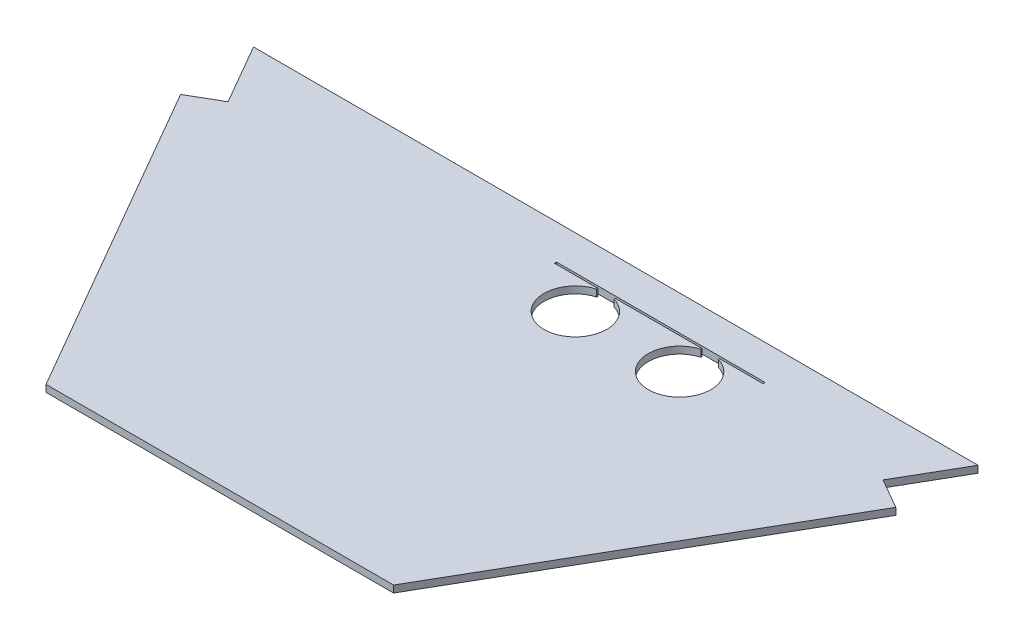
SolidWorks part; units mm, degrees
material "Ti-6Al-4VSolution treated and aged (SS)"
ref_plane "Front Plane" through (0, 0, 0) normal (0, 0, 1) x (1, 0, 0)
ref_plane "Top Plane" through (0, 0, 0) normal (0, 1, 0) x (1, 0, 0)
ref_plane "Right Plane" through (0, 0, 0) normal (1, 0, 0) x (0, 0, -1)
sketch "Sketch1" plane through (0, 0, 0) normal (0, 1, 0) x (1, 0, 0)
  line L1 (-271.1337, 569.6174) -> (771.1337, 569.6174)
  line L3 (500, 0) -> (0, 0)
  line L4 (0, 0) -> (-264.435, 458.0149)
  line L5 (-264.435, 458.0149) -> (-221.1337, 483.0149)
  line L6 (-221.1337, 483.0149) -> (-271.1337, 569.6174)
  line L7 (500, 0) -> (764.435, 458.0149)
  line L8 (764.435, 458.0149) -> (721.1337, 483.0149)
  line L9 (721.1337, 483.0149) -> (771.1337, 569.6174)
  dimension "D2" = 500
  dimension "D3" = 120
  dimension "D4" = 120
  dimension "D6" = 528.87
  dimension "D9" = 50
  dimension "D10" = 100
extrude "Boss-Extrude1" add sketch "Sketch1" along normal blind 10
sketch "Sketch2" plane through (0, 0, 0) normal (0, -1, 0) x (-1, 0, 0)
  line L0 (0, 0) -> (-500, 0) construction
  line L1 (-514.8837, 519.62) -> (-514.8837, 516.62)
  line L3 (-514.8837, 516.62) -> (-452.38, 516.62)
  line L4 (-214.8837, 516.62) -> (-214.8837, 519.62)
  line L5 (-214.8837, 519.62) -> (-514.8837, 519.62)
  line L6 (-302.38, 516.62) -> (-302.38, 514.849)
  line L7 (-277.38, 514.849) -> (-277.38, 516.62)
  line L8 (-277.38, 516.62) -> (-214.8837, 516.62)
  line L9 (-452.38, 516.62) -> (-452.38, 514.849)
  line L10 (-427.38, 516.62) -> (-427.38, 514.849)
  line L11 (-427.38, 516.62) -> (-302.38, 516.62)
  arc A0 (-452.38, 514.849) -> (-427.38, 514.849) centre (-439.88, 471.62) ccw
  arc A1 (-302.38, 514.849) -> (-277.38, 514.849) centre (-289.88, 471.62) ccw
  dimension "D1" = 471.62
  dimension "D2" = 90
  dimension "D3" = 150
  dimension "D4" = 3
  dimension "D5" = 300
  dimension "D6" = 439.88
  dimension "D7" = 256.25
  dimension "D8" = 25
  dimension "D9" = 25
extrude "Cut-Extrude6" cut sketch "Sketch2" against normal blind 10
